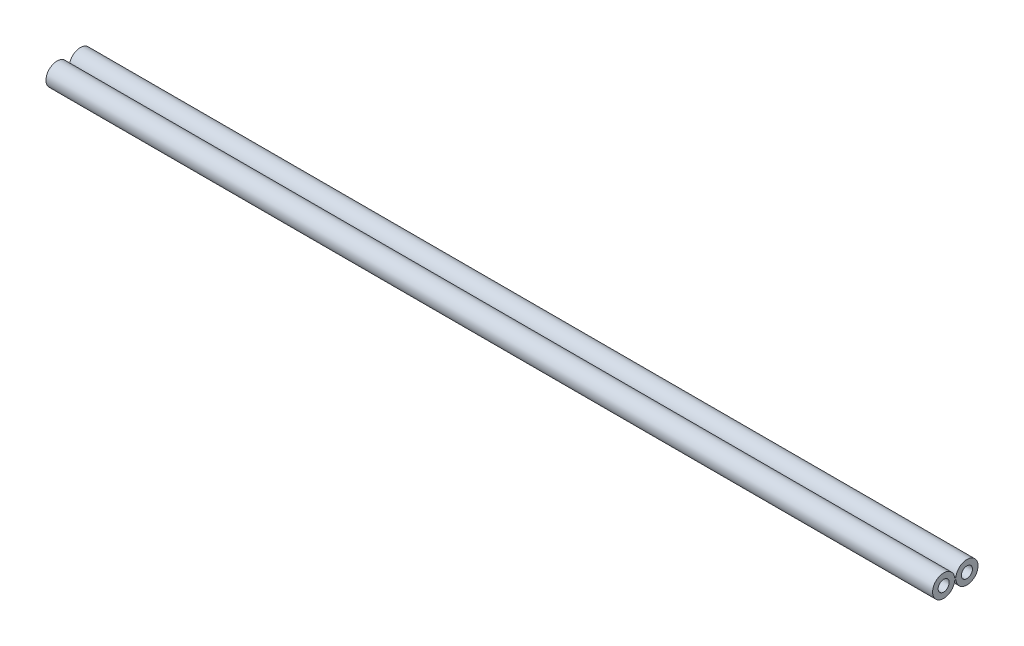
SolidWorks part; units mm, degrees
ref_plane "Front" through (0, 0, 0) normal (0, 0, 1) x (1, 0, 0)
ref_plane "Top" through (0, 0, 0) normal (0, 1, 0) x (1, 0, 0)
ref_plane "Right" through (0, 0, 0) normal (1, 0, 0) x (0, 0, -1)
sketch "Sketch1" plane through (0, 0, 0) normal (1, 0, 0) x (0, 0, -1)
  line L0 (1.5875, 0) -> (3.175, 0) construction
  line L1 (1.5875, 0) -> (3.175, 0) construction
  line L2 (2.3812, 0) -> (2.3812, 1.0672) construction
  circle A0 centre (0, 0) radius 3.175
  circle A1 centre (0, 0) radius 1.5875
  point P4 (3.175, 0)
  point P5 (1.5875, 0)
  dimension "OD" = 6.35
  dimension "ID" = 3.175
  dimension "Wall Thickness" = 1.5875
sketch "Sketch2" plane through (0, 0, 0) normal (0, 0, 1) x (1, 0, 0)
  line L0 (-127, 0) -> (127, 0) construction
  line L1 (0, -3.175) -> (0, 3.175) construction
  line L2 (0, -3.175) -> (0, 3.175) construction
  line L3 (-127, 3.175) -> (127, 3.175) construction
  line L4 (-127, 3.175) -> (-127, -3.175) construction
  point P2 (-119.0625, 0)
  point P3 (119.0625, 0)
  dimension "D1" = 7.9375
  dimension "D2" = 7.9375
sketch "Sketch3" plane through (0, 0, 0) normal (1, 0, 0) x (0, 0, -1)
  line L0 (0.1588, 0) -> (-0.1587, 0) construction
  line L1 (0, 0) -> (6.6675, 0) construction
  circle A4 centre (3.3337, 0) radius 1.5875
  circle A5 centre (3.3337, 0) radius 3.175
  circle A6 centre (0, 0) radius 1.5875 construction
  circle A7 centre (0, 0) radius 3.175 construction
  point P12 (6.5088, 0)
  point P13 (4.9213, 0)
  dimension "D1" = 0.3175
  dimension "D2" = 6.6675
  dimension "D3" = 3.3337
extrude "Boss-Extrude1" add sketch "Sketch3" along normal mid plane 254
pattern_linear "LPattern1" count 2 spacing 6.6675 along (0, 0, 1) of bodies 115
sketch "Sketch4" plane through (0, 0, 0) normal (1, 0, 0) x (0, 0, -1)
  line L0 (6.6675, 0.2381) -> (6.5088, 0.2381) construction
  line L1 (6.5088, -0.2381) -> (6.8262, -0.2381) construction
  line L2 (6.5088, -0.2381) -> (6.5088, 0.2381) construction
  line L3 (6.5088, 0.2381) -> (6.8262, 0.2381) construction
  line L4 (6.8262, -0.2381) -> (6.8262, 0.2381) construction
  line L5 (6.5088, -0.2381) -> (6.8262, 0.2381) construction
  line L6 (6.5088, 0.2381) -> (6.8262, -0.2381) construction
  line L11 (6.5881, 0.2381) -> (6.7469, 0.2381)
  line L12 (6.5881, -0.2381) -> (6.7469, -0.2381)
  line L13 (6.4921, 0.3248) -> (6.4921, -0.3248)
  line L14 (6.8429, 0.3248) -> (6.8429, -0.3248)
  line L15 (0.1754, 0.3248) -> (0.1754, -0.3248)
  line L16 (-0.0794, -0.2381) -> (0.0794, -0.2381)
  line L17 (-0.1754, 0.3248) -> (-0.1754, -0.3248)
  line L18 (-0.0794, 0.2381) -> (0.0794, 0.2381)
  line L19 (6.8429, 0.3248) -> (0.1754, 0.3248) construction
  circle A0 centre (3.3337, 0) radius 3.175 construction
  arc A1 (6.5881, 0.2381) -> (6.4921, 0.3248) centre (6.5881, 0.3347) cw
  arc A2 (6.7469, 0.2381) -> (6.8429, 0.3248) centre (6.7469, 0.3347) ccw
  arc A3 (6.5881, -0.2381) -> (6.4921, -0.3248) centre (6.5881, -0.3347) ccw
  arc A4 (6.7469, -0.2381) -> (6.8429, -0.3248) centre (6.7469, -0.3347) cw
  arc A5 (0.0794, -0.2381) -> (0.1754, -0.3248) centre (0.0794, -0.3347) cw
  arc A6 (-0.0794, -0.2381) -> (-0.1754, -0.3248) centre (-0.0794, -0.3347) ccw
  arc A7 (-0.0794, 0.2381) -> (-0.1754, 0.3248) centre (-0.0794, 0.3347) cw
  arc A8 (0.0794, 0.2381) -> (0.1754, 0.3248) centre (0.0794, 0.3347) ccw
  point P0 (6.6675, 0)
  dimension "D2" = 6.6675
  dimension "D1" = 2
  dimension "D3" = 0.4762
extrude "Boss-Extrude2" add sketch "Sketch4" along normal mid plane 254
sketch "Sketch5" plane through (0, 0, 0) normal (1, 0, 0) x (0, 0, -1)
  line L7 (6.4921, 0.3248) -> (6.8429, 0.3248)
  line L9 (6.4921, -0.3248) -> (6.8429, -0.3248)
  line L10 (6.8429, 0.3248) -> (6.8429, -0.3248)
  arc A0 (6.4921, 0.3248) -> (6.4921, -0.3248) centre (3.3337, 0) cw
  circle A1 centre (3.3337, 0) radius 3.175 construction
extrude "Cut-Extrude1" cut sketch "Sketch5" against normal through all both and the other way through all
equation "\"Number of Joined Tubes\"=2.000"
equation "\"D1@Boss-Extrude1\"=\"Length@Sketch2\""
equation "\"D1@Sketch2\"=\"OD@Sketch1\"*1.25"
equation "\"D2@Sketch2\"=\"D1@Sketch2\""
equation "\"D1@Sketch3\"=\"OD@Sketch1\"*0.05"
equation "\"D1@LPattern1\"=\"Number of Joined Tubes\""
equation "\"D3@LPattern1\"=\"D2@Sketch3\""
equation "\"D1@Boss-Extrude2\"=\"Length@Sketch2\""
equation "\"D1@Sketch4\"=\"Number of Joined Tubes\""
equation "\"D3@Sketch4\"=\"OD@Sketch1\"*0.075"
equation "\"D2@Sketch4\"=\"D2@Sketch3\""
equation "\"D3@Sketch3\"=(\"OD@Sketch1\"*1.05)*(\"Number of Joined Tubes\"-1)*0.5"
